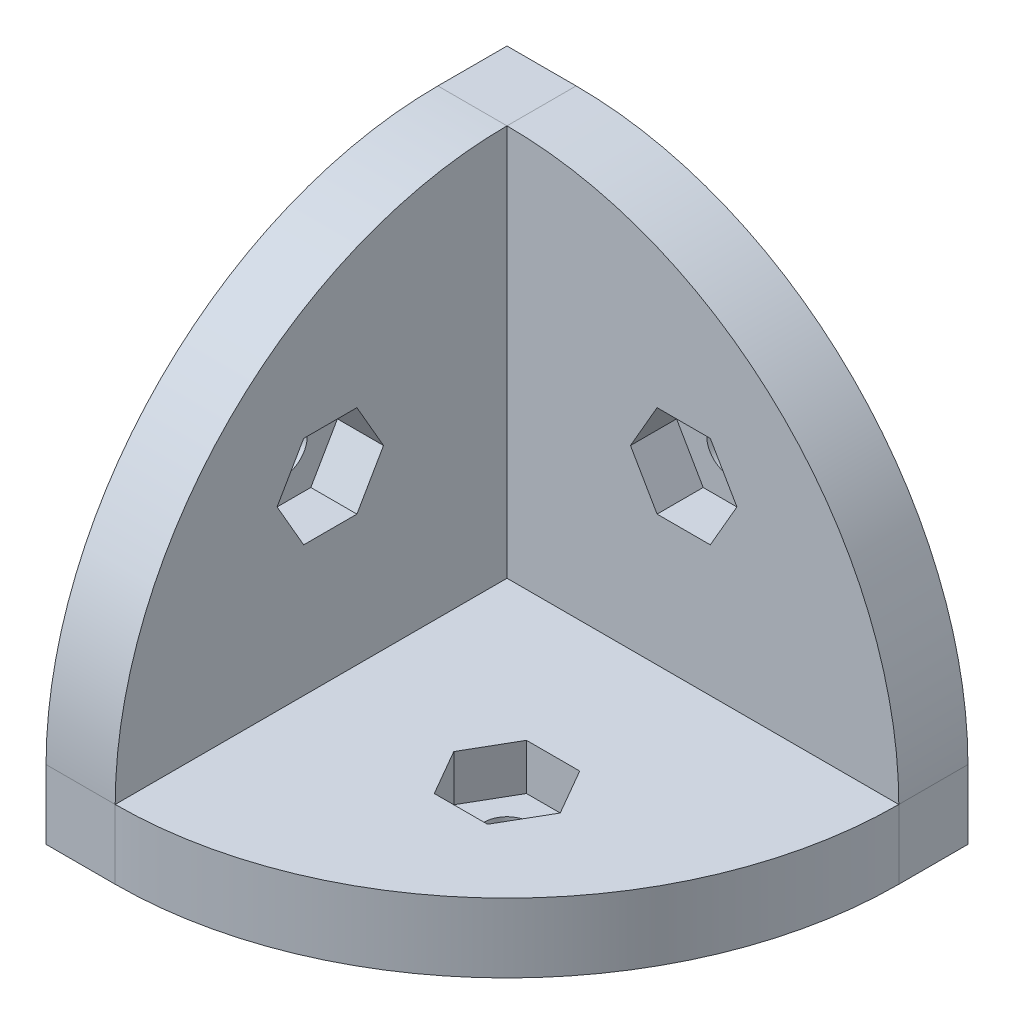
SolidWorks part; units mm, degrees
ref_plane "Front Plane" through (0, 0, 0) normal (0, 0, 1) x (1, 0, 0)
ref_plane "Top Plane" through (0, 0, 0) normal (0, 1, 0) x (1, 0, 0)
ref_plane "Right Plane" through (0, 0, 0) normal (1, 0, 0) x (0, 0, -1)
sketch "Sketch1" plane through (0, 0, 0) normal (0, 0, 1) x (1, 0, 0)
  line L0 (0, 0) -> (0, 30)
  line L1 (0, 30) -> (4.5, 30)
  line L2 (4.5, 30) -> (4.5, 4.5)
  line L3 (4.5, 4.5) -> (30, 4.5)
  line L4 (30, 4.5) -> (30, 0)
  line L5 (30, 0) -> (0, 0)
  dimension "D3" = 30
  dimension "D1" = 4.5
  dimension "D2" = 4.5
  dimension "D4" = 30
extrude "Boss-Extrude3" add sketch "Sketch1" along normal blind 30 contours L3 L4 L5 L0 L1 L2
sketch "Sketch6" plane through (0, 0, 0) normal (0, 0, -1) x (-1, 0, 0)
  line L0 (0, 0) -> (0, 30)
  line L1 (-4.5, 4.5) -> (-30, 4.5) construction
  line L3 (-30, 0) -> (-30, 4.5)
  line L4 (-4.5, 30) -> (0, 30)
  line L5 (-30, 0) -> (0, 0)
  arc A0 (-4.5, 30) -> (-30, 4.5) centre (-4.5, 4.5) ccw
extrude "Boss-Extrude4" add sketch "Sketch6" against normal blind 4.5
sketch "Sketch7" plane through (4.5, 0, 0) normal (1, 0, 0) x (0, 0, -1)
  line L1 (-30, 4.5) -> (-56.3308, 4.5)
  line L2 (-56.3308, 4.5) -> (-56.3308, 46.4479)
  line L3 (-56.3308, 46.4479) -> (-4.5, 46.4479)
  line L4 (-4.5, 46.4479) -> (-4.5, 30)
  arc A0 (-4.5, 30) -> (-30, 4.5) centre (-4.5, 4.5) ccw
extrude "Cut-Extrude3" cut sketch "Sketch7" against normal blind 4.5
sketch "Sketch8" plane through (0, 4.5, 0) normal (0, 1, 0) x (1, 0, 0)
  line L0 (4.5, -30) -> (30, -30) construction
  line L1 (4.5, -30) -> (4.5, -32.4711)
  line L2 (4.5, -32.4711) -> (33.3296, -32.4711)
  line L3 (33.3296, -32.4711) -> (33.3296, -4.5)
  line L4 (33.3296, -4.5) -> (30, -4.5)
  arc A0 (30, -4.5) -> (4.5, -30) centre (4.5, -4.5) cw
extrude "Cut-Extrude4" cut sketch "Sketch8" against normal blind 4.5
sketch "Sketch9" plane through (0, 0, 4.5) normal (0, 0, 1) x (1, 0, 0)
  circle A0 centre (16, 16) radius 1.5
  dimension "D1" = 3
  dimension "D2" = 16
  dimension "D3" = 16
extrude "Cut-Extrude5" cut sketch "Sketch9" against normal blind 4.5
sketch "Sketch10" plane through (0, 0, 4.5) normal (0, 0, 1) x (1, 0, 0)
  line L1 (19.4641, 16) -> (17.7321, 19)
  line L2 (17.7321, 19) -> (14.2679, 19)
  line L3 (14.2679, 19) -> (12.5359, 16)
  line L4 (12.5359, 16) -> (14.2679, 13)
  line L5 (14.2679, 13) -> (17.7321, 13)
  line L6 (17.7321, 13) -> (19.4641, 16)
  circle A0 centre (16, 16) radius 3 construction
  point P1 (0, 0)
  point P10 (0, 0)
  dimension "D1" = 6
extrude "Cut-Extrude6" cut sketch "Sketch10" against normal blind 3
sketch "Sketch12" plane through (0, 4.5, 0) normal (0, 1, 0) x (1, 0, 0)
  line L0 (0, 0) -> (4.5, 0) construction
  line L1 (0, -4.5) -> (0, 0) construction
  circle A0 centre (16, -16) radius 1.5
  dimension "D1" = 3
  dimension "D2" = 16
  dimension "D3" = 16
extrude "Cut-Extrude8" cut sketch "Sketch12" against normal through all
sketch "Sketch13" plane through (0, 4.5, 0) normal (0, 1, 0) x (1, 0, 0)
  line L1 (19.4641, -16) -> (17.7321, -13)
  line L2 (17.7321, -13) -> (14.2679, -13)
  line L3 (14.2679, -13) -> (12.5359, -16)
  line L4 (12.5359, -16) -> (14.2679, -19)
  line L5 (14.2679, -19) -> (17.7321, -19)
  line L6 (17.7321, -19) -> (19.4641, -16)
  circle A0 centre (16, -16) radius 3 construction
  dimension "D1" = 6
extrude "Cut-Extrude9" cut sketch "Sketch13" against normal blind 3
sketch "Sketch14" plane through (4.5, 0, 0) normal (1, 0, 0) x (0, 0, -1)
  line L0 (-4.5, 0) -> (0, 0) construction
  line L1 (0, 4.5) -> (0, 0) construction
  circle A0 centre (-16, 16) radius 1.5
  point P4 (-2.25, 0)
  dimension "D1" = 3
  dimension "D2" = 16
  dimension "D3" = 16
extrude "Cut-Extrude10" cut sketch "Sketch14" against normal through all
sketch "Sketch15" plane through (4.5, 0, 0) normal (1, 0, 0) x (0, 0, -1)
  line L1 (-19.4641, 16) -> (-17.7321, 13)
  line L2 (-17.7321, 13) -> (-14.2679, 13)
  line L3 (-14.2679, 13) -> (-12.5359, 16)
  line L4 (-12.5359, 16) -> (-14.2679, 19)
  line L5 (-14.2679, 19) -> (-17.7321, 19)
  line L6 (-17.7321, 19) -> (-19.4641, 16)
  circle A0 centre (-16, 16) radius 3 construction
  dimension "D1" = 6
extrude "Cut-Extrude11" cut sketch "Sketch15" against normal blind 3
